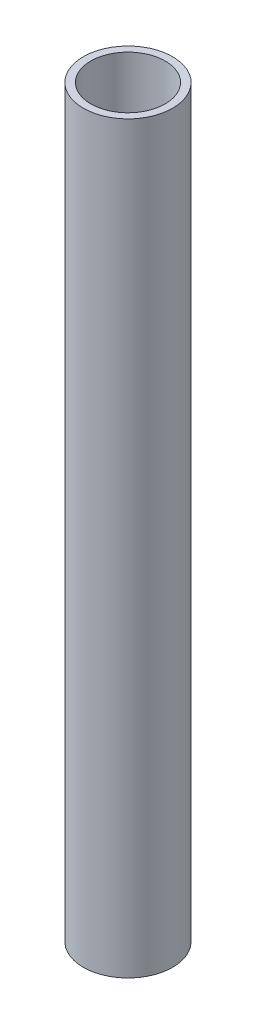
SolidWorks part; units mm, degrees
ref_plane "Front Plane" through (0, 0, 0) normal (0, 0, 1) x (1, 0, 0)
ref_plane "Top Plane" through (0, 0, 0) normal (0, 1, 0) x (1, 0, 0)
ref_plane "Right Plane" through (0, 0, 0) normal (1, 0, 0) x (0, 0, -1)
sketch "Sketch1" plane through (0, 0, 0) normal (0, 1, 0) x (1, 0, 0)
  circle A0 centre (0, 0) radius 15.24
  circle A1 centre (0, 0) radius 12.7
sketch3d "3DSketch2"
  line L0 (0, 0, 0) -> (0, -254, 0)
sweep "Sweep1" add profiles "Sketch1" path "3DSketch2"
